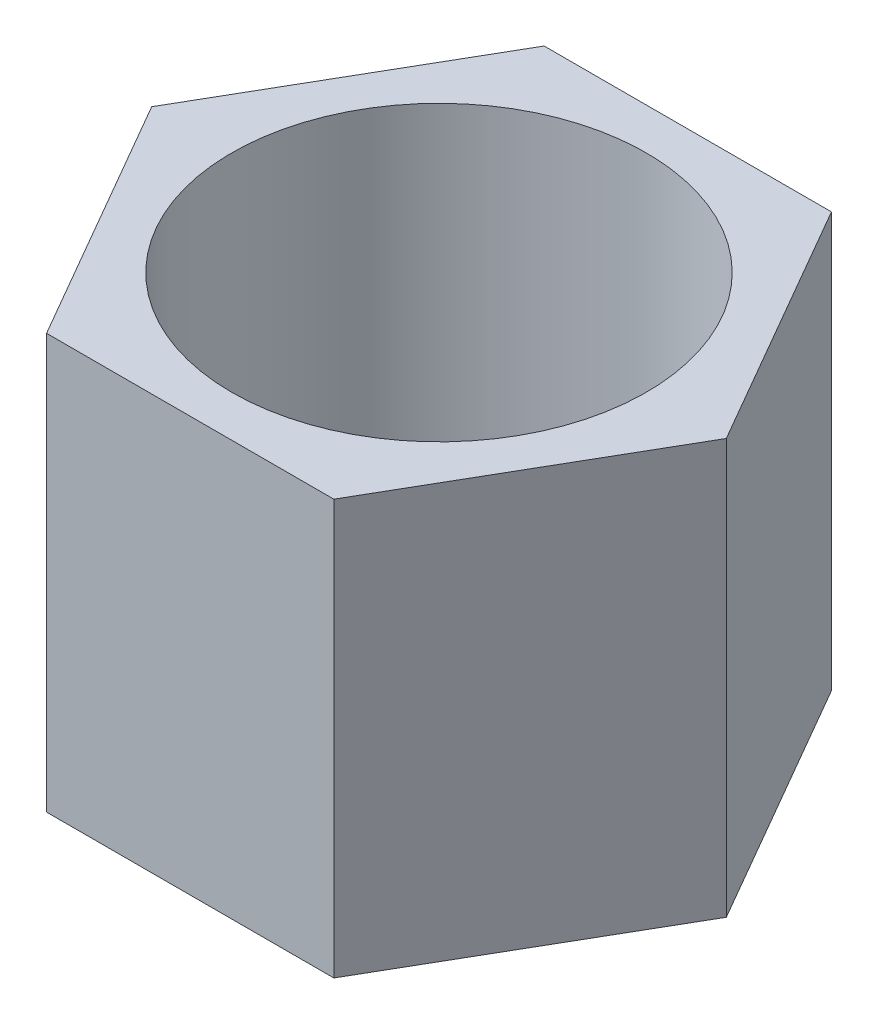
SolidWorks part; units mm, degrees
material "AISI 1010 Steel, hot rolled bar"
ref_plane "Front Plane" through (0, 0, 0) normal (0, 0, 1) x (1, 0, 0)
ref_plane "Top Plane" through (0, 0, 0) normal (0, 1, 0) x (1, 0, 0)
ref_plane "Right Plane" through (0, 0, 0) normal (1, 0, 0) x (0, 0, -1)
sketch "Sketch1" plane through (0, 0, 0) normal (0, 1, 0) x (1, 0, 0)
  line L1 (6.9282, 0) -> (3.4641, 6)
  line L2 (3.4641, 6) -> (-3.4641, 6)
  line L3 (-3.4641, 6) -> (-6.9282, 0)
  line L4 (-6.9282, 0) -> (-3.4641, -6)
  line L5 (-3.4641, -6) -> (3.4641, -6)
  line L6 (3.4641, -6) -> (6.9282, 0)
  circle A0 centre (0, 0) radius 6 construction
  circle A1 centre (0, 0) radius 5
  dimension "D1" = 12
  dimension "D2" = 10
extrude "Boss-Extrude1" add sketch "Sketch1" along normal blind 10
